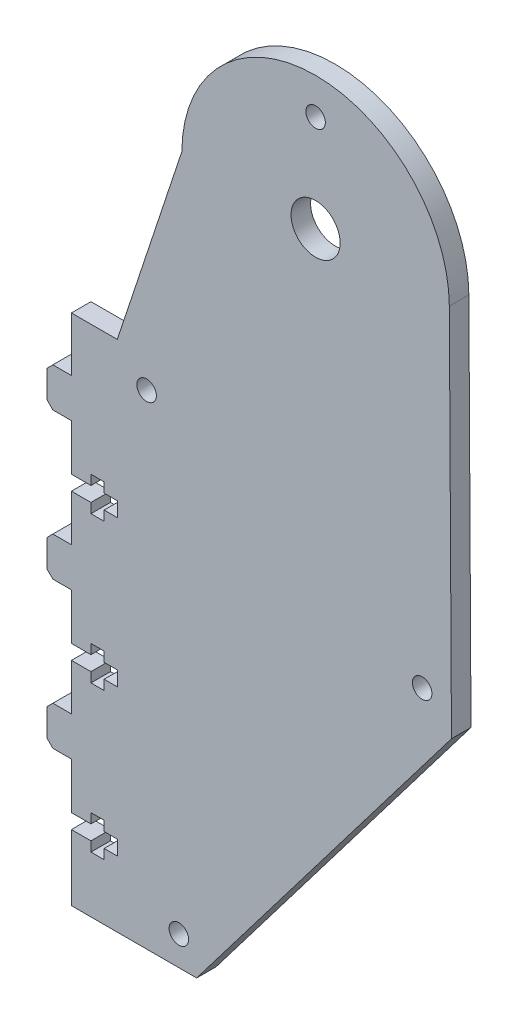
SolidWorks part; units mm, degrees
ref_plane "前视基准面" through (0, 0, 0) normal (0, 0, 1) x (1, 0, 0)
ref_plane "上视基准面" through (0, 0, 0) normal (0, 1, 0) x (1, 0, 0)
ref_plane "右视基准面" through (0, 0, 0) normal (1, 0, 0) x (0, 0, -1)
sketch "草图1" plane through (0, 0, 0) normal (0, 0, 1) x (1, 0, 0)
  line L4 (348.5429, 4.8543) -> (428.5429, 4.8543) construction
  line L11 (348.5429, 4.8543) -> (298.5429, 4.8543) construction
  line L15 (298.5515, -96.6457) -> (302.5515, -96.6457)
  line L16 (302.5515, -96.6457) -> (302.5515, -98.6442)
  line L17 (302.5515, -98.6442) -> (305.2515, -98.6442)
  line L18 (305.2515, -98.6442) -> (305.2515, -96.6457)
  line L19 (305.2515, -96.6457) -> (307.9515, -96.6457)
  line L20 (307.9515, -96.6457) -> (307.9515, -93.6457)
  line L21 (307.9515, -93.6457) -> (305.2515, -93.6457)
  line L22 (305.2515, -93.6457) -> (305.2515, -91.6472)
  line L23 (305.2515, -91.6472) -> (302.5515, -91.6472)
  line L24 (302.5515, -91.6472) -> (302.5515, -93.6457)
  line L25 (302.5515, -93.6457) -> (298.5515, -93.6457)
  line L27 (298.5429, -95.1457) -> (302.5429, -95.1457) construction
  line L28 (298.5515, -110.1457) -> (303.5515, -110.1457) construction
  line L29 (303.5515, -114.1457) -> (293.5515, -114.1457) construction
  line L30 (303.5515, -114.1457) -> (303.5515, -106.1457) construction
  line L31 (303.5515, -106.1457) -> (293.5515, -106.1457) construction
  line L32 (293.5515, -114.1457) -> (293.5515, -106.1457)
  line L33 (303.5515, -114.1457) -> (293.5515, -106.1457) construction
  line L34 (303.5515, -106.1457) -> (293.5515, -114.1457) construction
  line L35 (302.5515, -126.6457) -> (298.5515, -126.6457)
  line L36 (298.5515, -123.6457) -> (302.5515, -123.6457)
  line L37 (302.5515, -128.6442) -> (302.5515, -126.6457)
  line L38 (305.2515, -128.6442) -> (302.5515, -128.6442)
  line L39 (305.2515, -126.6457) -> (305.2515, -128.6442)
  line L40 (307.9515, -126.6457) -> (305.2515, -126.6457)
  line L41 (307.9515, -123.6457) -> (307.9515, -126.6457)
  line L42 (305.2515, -123.6457) -> (307.9515, -123.6457)
  line L43 (305.2515, -121.6473) -> (305.2515, -123.6457)
  line L44 (302.5515, -121.6473) -> (305.2515, -121.6473)
  line L45 (302.5515, -123.6457) -> (302.5515, -121.6473)
  line L46 (293.5515, -76.1457) -> (293.5515, -84.1457)
  line L47 (302.5515, -63.6457) -> (298.5515, -63.6457)
  line L48 (298.5515, -66.6457) -> (302.5515, -66.6457)
  line L49 (302.5515, -66.6457) -> (302.5515, -68.6442)
  line L50 (302.5515, -68.6442) -> (305.2515, -68.6442)
  line L51 (305.2515, -68.6442) -> (305.2515, -66.6457)
  line L52 (305.2515, -66.6457) -> (307.9515, -66.6457)
  line L53 (307.9515, -66.6457) -> (307.9515, -63.6457)
  line L54 (307.9515, -63.6457) -> (305.2515, -63.6457)
  line L55 (305.2515, -63.6457) -> (305.2515, -61.6472)
  line L56 (305.2515, -61.6472) -> (302.5515, -61.6472)
  line L57 (302.5515, -61.6472) -> (302.5515, -63.6457)
  line L58 (293.5515, -84.1457) -> (298.5515, -84.1457)
  line L59 (293.5515, -76.1457) -> (298.5515, -76.1457)
  line L60 (298.5515, -76.1457) -> (298.5515, -66.6457)
  line L61 (298.5515, -84.1457) -> (298.5515, -93.6457)
  line L62 (298.5515, -96.6457) -> (298.5515, -106.1457)
  line L63 (298.5515, -106.1457) -> (293.5515, -106.1457)
  line L64 (293.5515, -114.1457) -> (298.5515, -114.1457)
  line L65 (298.5515, -114.1457) -> (298.5515, -123.6457)
  line L66 (307.9515, -65.1457) -> (305.2429, -65.1457) construction
  line L67 (293.5515, -46.1457) -> (298.5515, -46.1457)
  line L68 (293.5515, -54.1457) -> (293.5515, -46.1457)
  line L69 (293.5515, -54.1457) -> (298.5515, -54.1457)
  line L70 (298.5515, -54.1457) -> (298.5515, -63.6457)
  line L78 (298.5515, -126.6457) -> (298.5515, -140.1457)
  line L79 (298.5515, -140.1457) -> (324.1947, -140.1457)
  line L81 (375.9264, 4.8543) -> (376.3645, -71.6457)
  line L84 (376.3645, -71.6457) -> (324.1947, -140.1457)
  line L85 (298.5515, -46.1457) -> (298.5515, -35.0457)
  line L87 (298.5515, -35.0457) -> (307.9429, -35.0457)
  line L88 (307.9429, -35.0457) -> (321.1593, 4.8543)
  circle A11 centre (348.5429, 4.8543) radius 5.03
  circle A14 centre (348.5429, 4.8543) radius 27.3835 construction
  arc A22 (375.9264, 4.8543) -> (321.1593, 4.8543) centre (348.5429, 4.6975) ccw
  circle A23 centre (348.5429, 24.6975) radius 2
  circle A24 centre (320.5515, -134.1457) radius 2
  circle A25 centre (370.3645, -65.6457) radius 2
  circle A26 centre (313.9429, -41.0457) radius 2
  point P30 (298.5515, -110.1457)
  dimension "D2" = 20
  dimension "D3" = 3
  dimension "D4" = 10.06
  dimension "D5" = 2.7
  dimension "D6" = 50
  dimension "D15" = 22
  dimension "D17" = 6
  dimension "D19" = 6
  dimension "D7" = 80
  dimension "D8" = 4
  dimension "D9" = 1.5
  dimension "D10" = 15
  dimension "D11" = 8
  dimension "D12" = 10
  dimension "D13" = 100
  dimension "D14" = 13.5
  dimension "D16" = 6
  dimension "D18" = 6
  dimension "D20" = 6
extrude "凸台-拉伸1" add sketch "草图1" along normal blind 4
sketch "草图2" plane through (298.5515, 0, 0) normal (-1, 0, 0) x (0, 0, 1)
  line L0 (2, -66.6457) -> (2, -63.6457)
  line L1 (4, -66.6457) -> (0, -66.6457) construction
  line L2 (4, -63.6457) -> (0, -63.6457) construction
  circle A0 centre (2, -65.1457) radius 1.5
sketch "草图3" plane through (0, 0, 4) normal (0, 0, 1) x (1, 0, 0)
  line L3 (293.5515, -46.1457) -> (293.5515, -54.1457) construction
  line L5 (293.5515, -46.1457) -> (294.7515, -46.1457)
  line L6 (298.5515, -46.1457) -> (293.5515, -46.1457) construction
  line L7 (294.7515, -46.1457) -> (293.5515, -47.3457)
  line L8 (293.5515, -47.3457) -> (293.5515, -46.1457)
  line L9 (294.7515, -84.1457) -> (293.5515, -84.1457)
  line L10 (293.5515, -84.1457) -> (298.5515, -84.1457) construction
  line L11 (293.5515, -84.1457) -> (293.5515, -82.9457)
  line L12 (293.5515, -76.1457) -> (293.5515, -84.1457) construction
  line L13 (293.5515, -82.9457) -> (294.7515, -84.1457)
  line L14 (293.5515, -77.3457) -> (293.5515, -76.1457)
  line L15 (293.5515, -76.1457) -> (294.7515, -76.1457)
  line L16 (298.5515, -76.1457) -> (293.5515, -76.1457) construction
  line L17 (294.7515, -76.1457) -> (293.5515, -77.3457)
  line L19 (294.7515, -54.1457) -> (293.5515, -54.1457)
  line L20 (293.5515, -114.1457) -> (293.5515, -112.9457)
  line L21 (293.5515, -106.1457) -> (293.5515, -114.1457) construction
  line L23 (293.5515, -107.3457) -> (293.5515, -106.1457)
  line L24 (293.5515, -106.1457) -> (294.7515, -106.1457)
  line L25 (298.5515, -106.1457) -> (293.5515, -106.1457) construction
  line L26 (294.7515, -106.1457) -> (293.5515, -107.3457)
  line L27 (293.5515, -112.9457) -> (294.7515, -114.1457)
  line L28 (293.5515, -114.1457) -> (298.5515, -114.1457) construction
  line L29 (294.7515, -114.1457) -> (293.5515, -114.1457)
  line L30 (293.5515, -54.1457) -> (298.5515, -54.1457) construction
  line L31 (293.5515, -54.1457) -> (293.5515, -52.9457)
  line L32 (293.5515, -52.9457) -> (294.7515, -54.1457)
  dimension "D1" = 1.2
extrude "切除-拉伸1" cut sketch "草图3" against normal blind 4
